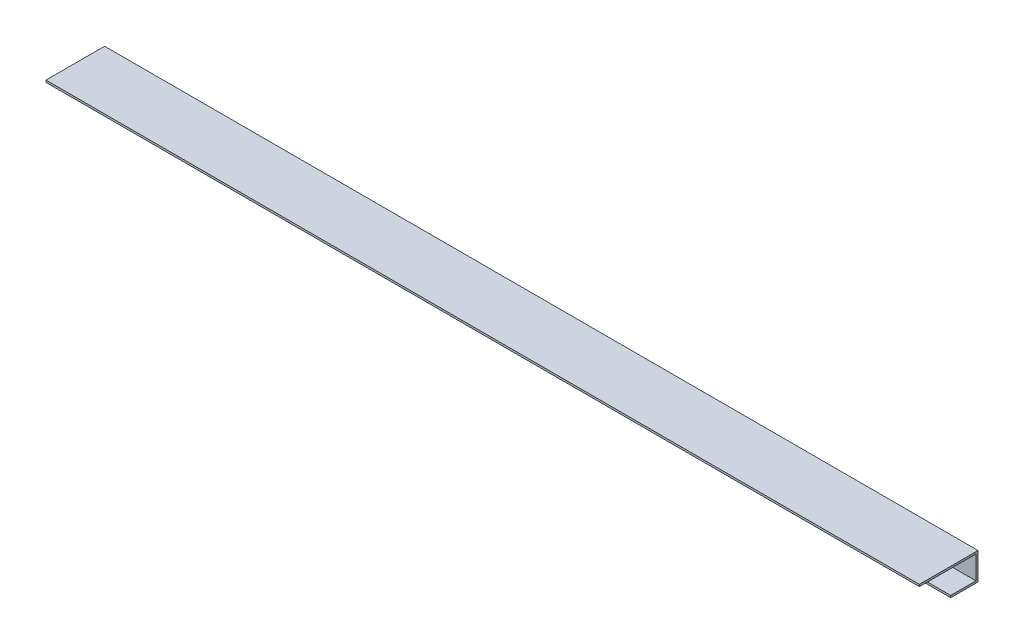
SolidWorks part; units mm, degrees
ref_plane "Front Plane" through (0, 0, 0) normal (0, 0, 1) x (1, 0, 0)
ref_plane "Top Plane" through (0, 0, 0) normal (0, 1, 0) x (1, 0, 0)
ref_plane "Right Plane" through (0, 0, 0) normal (1, 0, 0) x (0, 0, -1)
sketch "Sketch1" plane through (0, 0, 0) normal (1, 0, 0) x (0, 0, -1)
  line L0 (0, 0) -> (58, 0)
  line L1 (58, 0) -> (58, -27)
  line L2 (58, -27) -> (31, -27)
  line L3 (0, -2) -> (56, -2)
  line L4 (56, -2) -> (56, -25)
  line L5 (56, -25) -> (31, -25)
  line L6 (0, 0) -> (0, -2)
  line L7 (31, -25) -> (31, -27)
  dimension "D1" = 2
  dimension "D2" = 58
  dimension "D3" = 27
  dimension "D4" = 27
extrude "Boss-Extrude1" add sketch "Sketch1" along normal blind 864
equation "\"door_base_short7_BL_Single_width\"=864"
equation "\"D1@Boss-Extrude1\"=\"door_base_short7_BL_Single_width\""
equation "\"CarBeamWidth\"=700.0"
equation "\"WheelWidth\"=650.0"
equation "\"Wheel_FrontBoxDistance\"=1390.0"
equation "\"boxLength\"=5100.0"
equation "\"boxWidth\"=1930.0"
equation "\"MetalSheet_3mm_length\"=5030.0"
equation "\"MetalSheet_3mm_width\"=1923.0"
equation "\"MetalSheet_3mm_FloorCut_L_length\"=1764.0"
equation "\"MetalSheet_3mm_FloorCut_L_disdance\"=1665.0"
equation "\"MetalSheet_3mm_FloorCut_R_length\"=1764.0"
equation "\"MetalSheet_3mm_FloorCut_R_disdance\"=1665.0"
equation "\"indoorHeight\"=1940.0"
equation "\"indoorHeight_para\"=25.0"
equation "\"rearLightHeight_para\"=265.0"
equation "\"haveDoor_R\"=1"
equation "\"side_door_bottom_R_3mm_length\"=1934.0"
equation "\"side_door_bottom_R_3mm_toFrontDistance\"=1583.0"
equation "\"1Bar_Side_RF_3mm_length\"=1493.0"
equation "\"1Bar_Side_RB_3mm_length\"=1493.0"
equation "\"DoorSeparator_RF_3mm_withHinge_toFrontDistance\"=1673.0"
equation "\"DoorSeparator_RF_3mm_withHinge_exist\"=1"
equation "\"DoorSeparator_RB_3mm_withHinge_toFrontDistance\"=3427.0"
equation "\"DoorSeparator_RB_3mm_withHinge_exist\"=1"
equation "\"Door_R1_L_open_Single_toFrontDistance\"=2547.5"
equation "\"Door_R1_L_open_Single_exist\"=1"
equation "\"door_base_long7_R1_L_open_Single_height\"=1890.0"
equation "\"door_base_short7_R1_L_open_Single_height\"=1890.0"
equation "\"door_base_short7_R1_L_open_Single_width\"=864"
equation "\"Door_R1_R_open_Single_toFrontDistance\"=3422.0"
equation "\"Door_R1_R_open_Single_exist\"=1"
equation "\"door_base_long7_R1_R_open_Single_height\"=1890.0"
equation "\"door_base_short7_R1_R_open_Single_height\"=1890.0"
equation "\"door_base_short7_R1_R_open_Single_width\"=864"
equation "\"x\"=66.0"
equation "\"door_base_double_BL_height\"=1890.0"
equation "\"door_base_short7_BL_Single_height\"=1890.0"
equation "\"door_base_long7_BR_Single_height\"=1890.0"
equation "\"door_base_short7_BR_Single_height\"=1890.0"
equation "\"door_base_short7_BR_Single_width\"=864"
equation "\"da\"=62.0"
equation "\"SquareTube_length\"=1923.0"
equation "\"channelSteel_length\"=5030.0"
equation "\"SquareTube_inFront_AvgDistance\"=285.0"
equation "\"SquareTube_inFront_TotalCount\"=5"
equation "\"SquareTube_inFront1_cutDepth50_R\"=0.5"
equation "\"SquareTube_inFront1_cutDepth50_L\"=0.5"
equation "\"SquareTube_inFront2_cutDepth50_R\"=0.5"
equation "\"SquareTube_inFront2_cutDepth50_L\"=0.5"
equation "\"SquareTube_inFront3_cutDepth50_R\"=0.5"
equation "\"SquareTube_inFront3_cutDepth50_L\"=0.5"
equation "\"SquareTube_inFront4_cutDepth50_R\"=0.5"
equation "\"SquareTube_inFront4_cutDepth50_L\"=0.5"
equation "\"SquareTube_inFront5_cutDepth50_R\"=50"
equation "\"SquareTube_inFront5_cutDepth50_L\"=50"
equation "\"SquareTube_inFront6_cutDepth50_R\"=50"
equation "\"SquareTube_inFront6_cutDepth50_L\"=50"
equation "\"SquareTube_inFront7_cutDepth50_R\"=50"
equation "\"SquareTube_inFront7_cutDepth50_L\"=50"
equation "\"SquareTube_inFront8_cutDepth50_R\"=50"
equation "\"SquareTube_inFront8_cutDepth50_L\"=50"
equation "\"SquareTube_inFront9_cutDepth50_R\"=50"
equation "\"SquareTube_inFront9_cutDepth50_L\"=50"
equation "\"SquareTube_inFront10_cutDepth50_R\"=50"
equation "\"SquareTube_inFront10_cutDepth50_L\"=50"
equation "\"SquareTube_inFront11_cutDepth50_R\"=50"
equation "\"SquareTube_inFront11_cutDepth50_L\"=50"
equation "\"SquareTube_inFront12_cutDepth50_R\"=50"
equation "\"SquareTube_inFront12_cutDepth50_L\"=50"
equation "\"SquareTube_inFront13_cutDepth50_R\"=50"
equation "\"SquareTube_inFront13_cutDepth50_L\"=50"
equation "\"SquareTube_inFront14_cutDepth50_R\"=50"
equation "\"SquareTube_inFront14_cutDepth50_L\"=50"
equation "\"SquareTube_inBack_AvgDistance\"=333.125"
equation "\"SquareTube_inBack_TotalCount\"=9"
equation "\"SquareTube_inBack1_cutDepth50_R\"=50"
equation "\"SquareTube_inBack1_cutDepth50_L\"=50"
equation "\"SquareTube_inBack2_cutDepth50_R\"=50"
equation "\"SquareTube_inBack2_cutDepth50_L\"=50"
equation "\"SquareTube_inBack3_cutDepth50_R\"=50"
equation "\"SquareTube_inBack3_cutDepth50_L\"=50"
equation "\"SquareTube_inBack4_cutDepth50_R\"=50"
equation "\"SquareTube_inBack4_cutDepth50_L\"=50"
equation "\"SquareTube_inBack5_cutDepth50_R\"=50"
equation "\"SquareTube_inBack5_cutDepth50_L\"=50"
equation "\"SquareTube_inBack6_cutDepth50_R\"=0.5"
equation "\"SquareTube_inBack6_cutDepth50_L\"=0.5"
equation "\"SquareTube_inBack7_cutDepth50_R\"=0.5"
equation "\"SquareTube_inBack7_cutDepth50_L\"=0.5"
equation "\"SquareTube_inBack8_cutDepth50_R\"=0.5"
equation "\"SquareTube_inBack8_cutDepth50_L\"=0.5"
